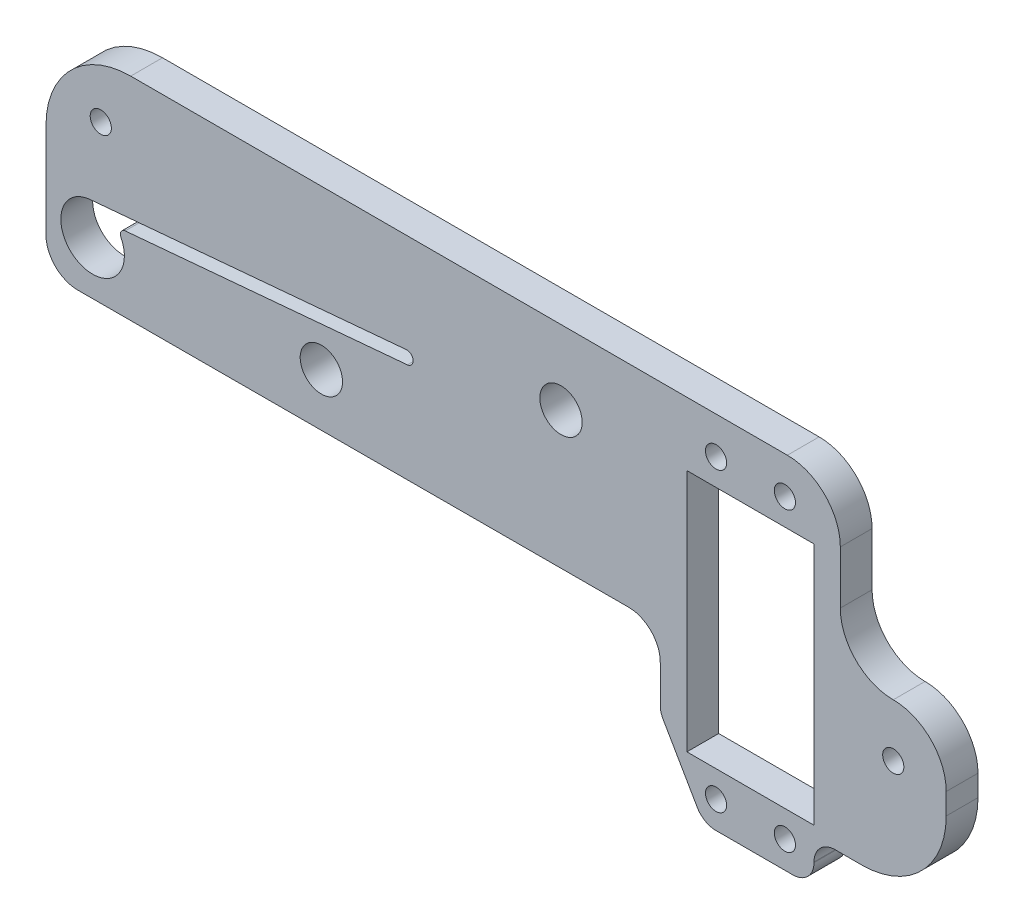
SolidWorks part; units mm, degrees
ref_plane "前视基准面" through (0, 0, 0) normal (0, 0, 1) x (1, 0, 0)
ref_plane "上视基准面" through (0, 0, 0) normal (0, 1, 0) x (1, 0, 0)
ref_plane "右视基准面" through (0, 0, 0) normal (1, 0, 0) x (0, 0, -1)
sketch "草图1" plane through (0, 0, 0) normal (0, 0, 1) x (1, 0, 0)
  line L0 (46.516, -14) -> (46.516, 9)
  line L1 (34.516, 9) -> (34.516, -14)
  line L2 (46.516, 9) -> (34.516, 9)
  line L3 (32, -8) -> (32, -11.4641)
  line L4 (48.516, -15) -> (51, -15)
  line L5 (59, -7) -> (59, -5)
  line L6 (49, 5) -> (49, 10)
  line L7 (44, 15) -> (-18, 15)
  line L8 (-26, 7) -> (-26, -2)
  line L9 (-23, -5) -> (28.9998, -4.9241)
  line L10 (46.516, -14) -> (34.516, -14)
  line L11 (-21.8658, 2.9882) -> (8.0162, 5.6465)
  line L12 (0, 0) -> (-21.6, 0) construction
  line L14 (8.1225, 4.4512) -> (-18.5227, 2.0809)
  line L15 (46.516, -2.5) -> (28.0312, -2.5) construction
  line L18 (46.516, -17.0599) -> (46.516, -17)
  line L19 (32.268, -12.4641) -> (35.5001, -18.0602)
  line L20 (37.232, -19.0599) -> (44.516, -19.0599)
  arc A1 (51, -15) -> (59, -7) centre (51, -7) ccw
  arc A2 (59, -5) -> (54, 0) centre (54, -5) ccw
  arc A3 (49, 5) -> (54, 0) centre (54, 5) ccw
  arc A4 (49, 10) -> (44, 15) centre (44, 10) ccw
  arc A5 (-18, 15) -> (-26, 7) centre (-18, 7) ccw
  arc A6 (-26, -2) -> (-23, -5) centre (-23, -2) ccw
  arc A7 (32, -8) -> (28.9998, -4.9241) centre (29.001, -7.9241) ccw
  circle A8 centre (-20.8284, 9.8284) radius 1
  arc A10 (-21.8658, 2.9882) -> (-18.9243, 1.3567) centre (-21.6, 0) ccw
  circle A11 centre (0, 0) radius 2
  circle A12 centre (22.6274, 8) radius 2
  circle A13 centre (37.266, 11.5) radius 1
  circle A14 centre (43.766, 11.5) radius 1
  circle A15 centre (54, -5) radius 1
  arc A16 (-18.5227, 2.0809) -> (-18.9243, 1.3567) centre (-18.4784, 1.5828) ccw
  arc A17 (8.1225, 4.4512) -> (8.0162, 5.6465) centre (8.0693, 5.0488) ccw
  circle A18 centre (43.766, -16.5) radius 1
  circle A19 centre (37.266, -16.5) radius 1
  arc A22 (46.516, -17) -> (48.516, -15) centre (48.516, -17) cw
  arc A24 (32, -11.4641) -> (32.268, -12.4641) centre (33.9994, -11.4641) ccw
  arc A25 (37.232, -19.0599) -> (35.5001, -18.0602) centre (37.232, -17.0599) cw
  arc A26 (44.516, -19.0599) -> (46.516, -17.0599) centre (44.516, -17.0599) ccw
  point P4 (36.0775, -19.056)
  point P54 (32, -20)
  point P64 (32, -12)
  dimension "D3" = 6
  dimension "D8" = 0.5
  dimension "D9" = 8
  dimension "D10" = 2
  dimension "D11" = 2
  dimension "D1" = 21.6
  dimension "D2" = 24
  dimension "D4" = 30
  dimension "D5" = 5
  dimension "D6" = 21.6
  dimension "D7" = 1.2
extrude "凸台-拉伸1" add sketch "草图1" along normal blind 3
